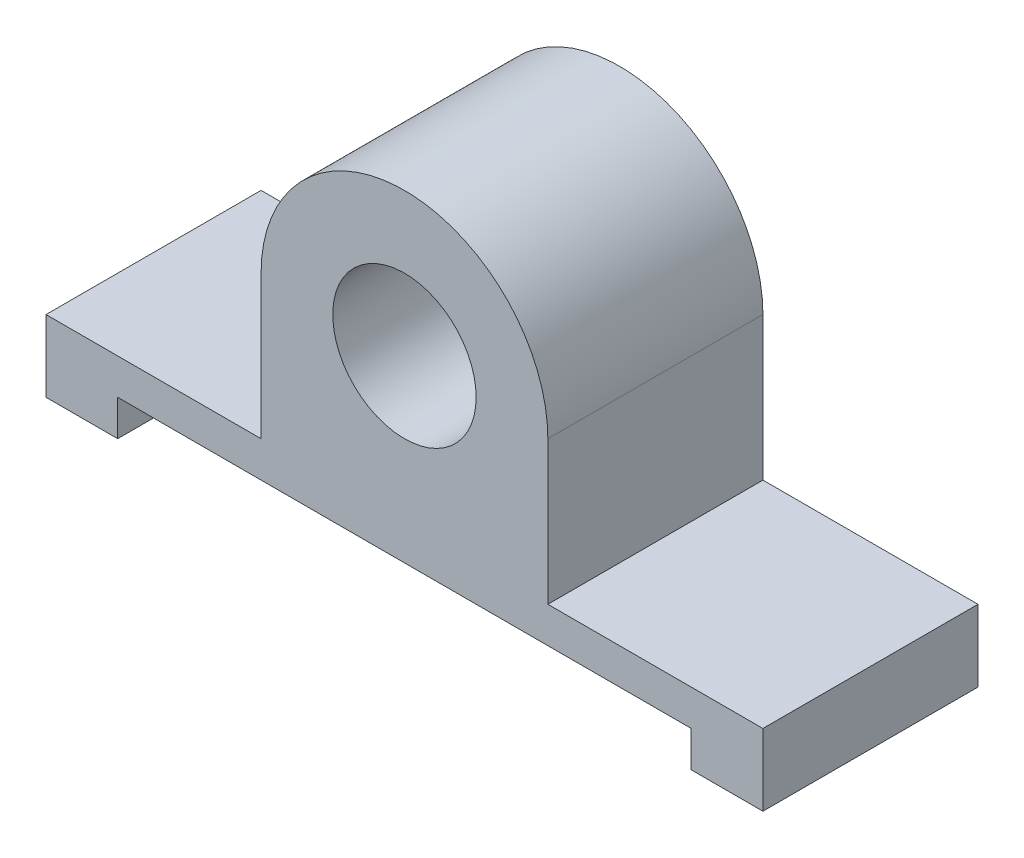
SolidWorks part; units mm, degrees
ref_plane "Front Plane" through (0, 0, 0) normal (0, 0, 1) x (1, 0, 0)
ref_plane "Top Plane" through (0, 0, 0) normal (0, 1, 0) x (1, 0, 0)
ref_plane "Right Plane" through (0, 0, 0) normal (1, 0, 0) x (0, 0, -1)
sketch "Sketch1" plane through (0, 0, 0) normal (0, 0, 1) x (1, 0, 0)
  line L0 (0, 0) -> (0, 19212.5674) construction
  line L13 (40, 0) -> (-40, 0)
  line L14 (-40, 0) -> (-40, -5)
  line L15 (-40, -5) -> (-50, -5)
  line L16 (-50, -5) -> (-50, 5)
  line L17 (-50, 5) -> (-20, 5)
  line L18 (-20, 5) -> (-20, 25)
  line L19 (20, 5) -> (20, 25)
  line L20 (50, 5) -> (20, 5)
  line L21 (40, -5) -> (50, -5)
  line L22 (50, -5) -> (50, 5)
  line L23 (40, 0) -> (40, -5)
  arc A2 (-20, 25) -> (20, 25) centre (0, 25) cw
  circle A3 centre (0, 25) radius 10
  point P14 (0, 0)
  dimension "D2" = 20
  dimension "D1" = 20
  dimension "D3" = 5
  dimension "D4" = 10
  dimension "D5" = 80
extrude "Boss-Extrude1" add sketch "Sketch1" along normal blind 30
